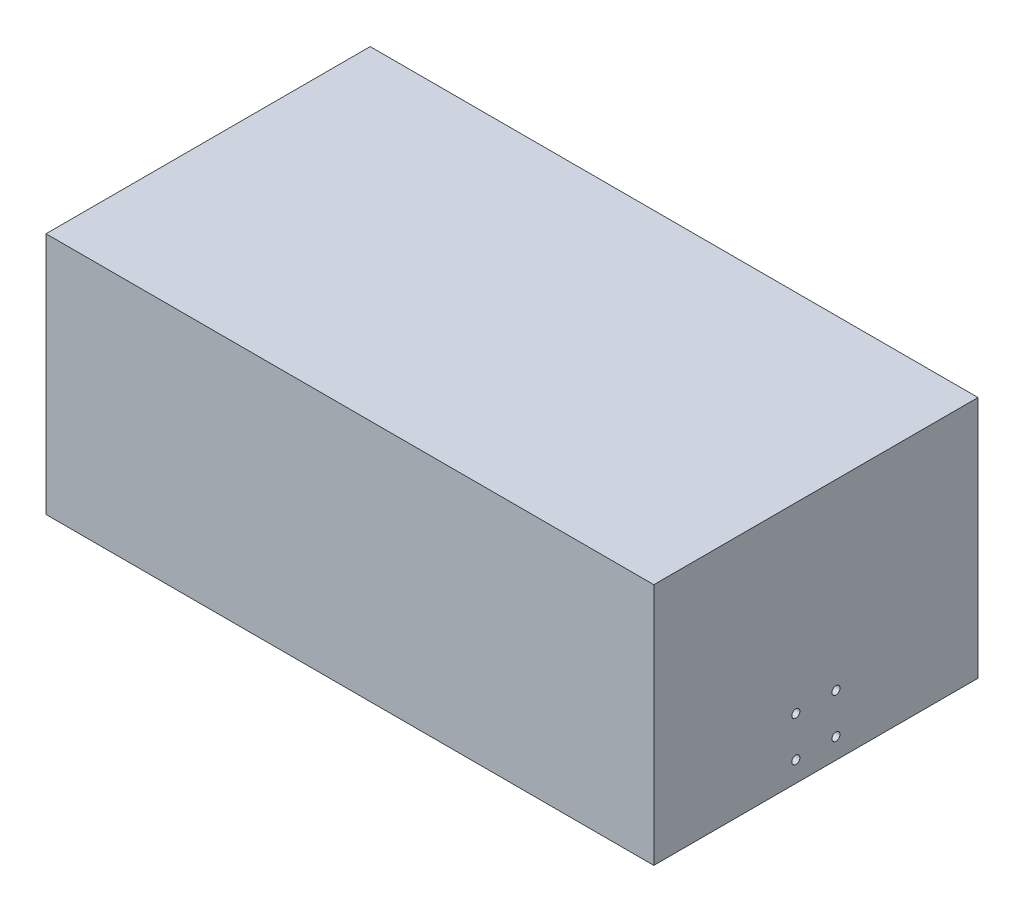
SolidWorks part; units mm, degrees
ref_plane "Спереди" through (0, 0, 0) normal (0, 0, 1) x (1, 0, 0)
ref_plane "Сверху" through (0, 0, 0) normal (0, 1, 0) x (1, 0, 0)
ref_plane "Справа" through (0, 0, 0) normal (1, 0, 0) x (0, 0, -1)
sketch "Эскиз1" plane through (0, 0, 0) normal (0, 1, 0) x (1, 0, 0)
  line L1 (0, 0) -> (150, 0)
  line L2 (0, 0) -> (0, 80)
  line L3 (0, 80) -> (150, 80)
  line L4 (150, 0) -> (150, 80)
extrude "Бобышка-Вытянуть1" add sketch "Эскиз1" along normal blind 60
sketch "Эскиз2" plane through (150, 0, 0) normal (1, 0, 0) x (0, 0, -1)
  line L0 (0, 0) -> (80, 0) construction
  line L2 (40, 17) -> (33, 10) construction
  line L3 (36.5, 13.5) -> (35.0503, 14.9497) construction
  line L4 (36.5, 13.5) -> (44.9497, 5.0503) construction
  line L5 (40, 10) -> (44.9497, 14.9497) construction
  line L6 (40, 10) -> (35.0503, 5.0503) construction
  circle A0 centre (40, 10) radius 7 construction
  circle A1 centre (40, 10) radius 8 construction
  circle A2 centre (35.0503, 14.9497) radius 1
  circle A3 centre (44.9497, 14.9497) radius 1
  circle A4 centre (44.9497, 5.0503) radius 1
  circle A5 centre (35.0503, 5.0503) radius 1
  point P6 (40, 0)
  dimension "D1" = 14
  dimension "D2" = 16
  dimension "D3" = 10
extrude "Вырез-Вытянуть2" cut sketch "Эскиз2" against normal blind 10
